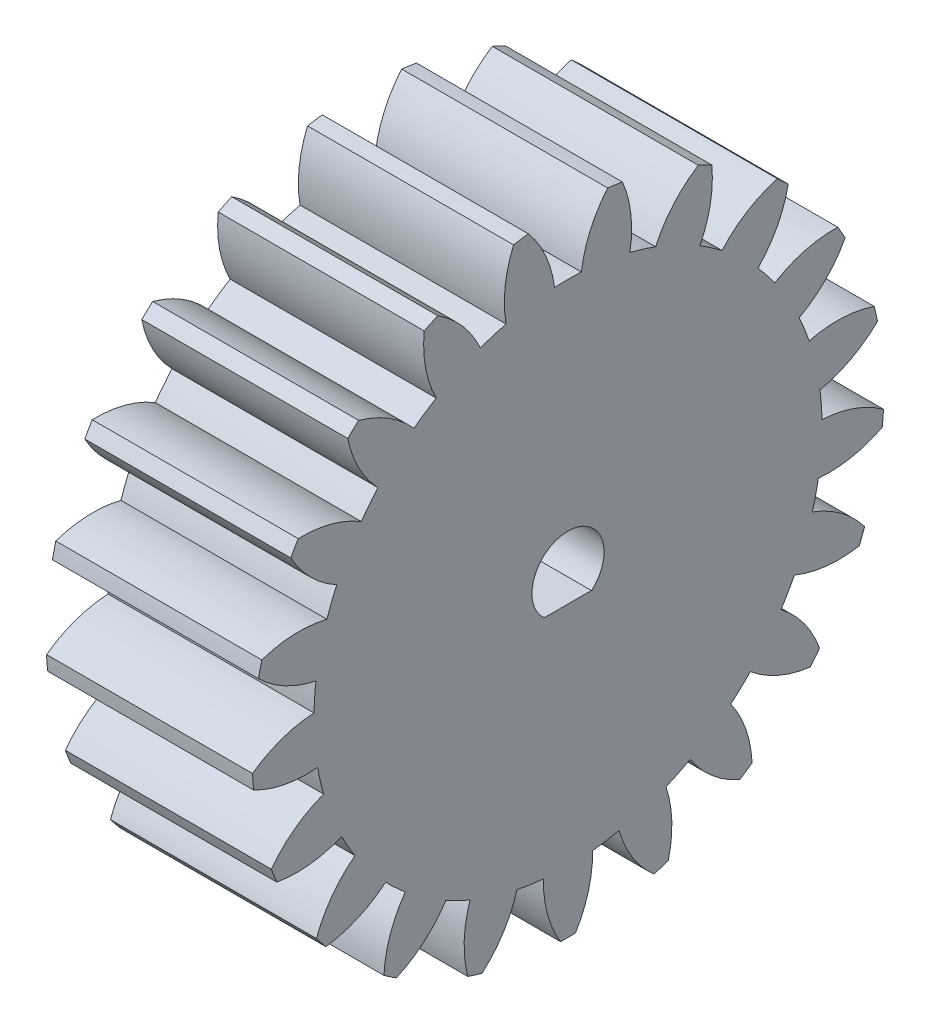
SolidWorks part; units mm, degrees
ref_plane "Plane1" through (0, 0, 0) normal (0, 0, 1) x (1, 0, 0)
ref_plane "Plane2" through (0, 0, 0) normal (0, 1, 0) x (1, 0, 0)
ref_plane "Plane3" through (0, 0, 0) normal (1, 0, 0) x (0, 0, -1)
other "Configuration Table"
sketch "HoldingSke" plane through (0, 0, 0) normal (0, 1, 0) x (1, 0, 0)
  line L0 (0, 0) -> (0.4668, -0.1792)
  line L1 (-15, 0) -> (100, 0) construction
  line L2 (0, 0) -> (-2.1039, 2.3779)
  line L3 (0, 0) -> (-11.863, 4.5341)
  line L4 (0, 0) -> (8.0624, 3.0949)
  line L5 (0, 0) -> (-46.8476, -17.4728)
  line L6 (0, 0) -> (-12.4344, -8.3896)
  line L7 (-2.1039, 2.3779) -> (8.6586, 51.2059)
  line L8 (-76.2, 54.61) -> (-75.3, 54.61)
  line L9 (-71.009, 38.7566) -> (-53.1078, 45.2721)
  line L10 (-76.2, 71.12) -> (104.1128, 71.12)
  line L11 (0, 0) -> (-15, 0)
  line L12 (-76.2, 101.6) -> (-76.133, 101.6)
  line L13 (24.9733, 27.94) -> (52.9518, 28.4284)
  line L14 (24.9733, 27.94) -> (24.9743, 27.94)
  line L15 (24.9733, 27.94) -> (100.4006, 29.5858)
  line L16 (-63.627, -2) -> (-12.827, -2)
  circle A0 centre (0, 0) radius 2.5
  circle A1 centre (0, 0) radius 18.499
  circle A2 centre (0, 0) radius 37.5
  circle A3 centre (0, 0) radius 2.5
  dimension "MHD" = 36.998
  dimension "Hub_dia" = 75
  dimension "Bore" = 5
  dimension "MBD" = 5
  dimension "Num_teeth" = 21
  dimension "Pitch" = 0.5
  dimension "Overall_len" = 50
  dimension "Show_teeth" = 21
  dimension "Thickness" = 15
  dimension "OAL" = 50.0001
  dimension "T_dim" = 0.9
  dimension "Ap" = 20
  dimension "H" = 19.05
  dimension "Pitch_radius" = 180.3128
  dimension "Width" = 15
  dimension "Backlash" = 0.067
  dimension "Addendum_fac" = 1
  dimension "Dedendum_fac" = 1.25
  dimension "Clearance_fac" = 0.25
  dimension "Dedendum_add" = 0.001
  dimension "Module" = 2
sketch "BasProSke" plane through (0, 0, 0) normal (0, 1, 0) x (1, 0, 0)
  line L0 (-10, 0) -> (60, 0) construction
  line L1 (0, 0) -> (0, 23)
  line L2 (0, 0) -> (15, 0)
  line L3 (15, 0) -> (15, 23)
  line L4 (15, 23) -> (0, 23)
  dimension "Thickness" = 15
  dimension "Diameter" = 46
revolve "Base-Revolve" add sketch "BasProSke" angle 360 about L0
sketch "TooCutSke" plane through (0, 0, 0) normal (1, 0, 0) x (0, 0, -1)
  line L1 (0, 0) -> (0, 107) construction
  line L2 (0, 0) -> (-1.6865, 20.9322) construction
  line L3 (0, 0) -> (-6.2448, 41.4315) construction
  line L4 (-1.6865, 20.9322) -> (-3.1224, 20.7157) construction
  arc A0 (0.9768, 18.4732) -> (-0.9768, 18.4732) centre (0, 0) ccw
  arc A1 (2.908, 22.841) -> (-2.908, 22.841) centre (0, 0) ccw
  circle A2 centre (0, 0) radius 21 construction
  circle A3 centre (0, 0) radius 19.7335 construction
  arc A4 (-0.9768, 18.4732) -> (-2.908, 22.841) centre (-9.308, 17.4004) ccw
  arc A5 (2.908, 22.841) -> (0.9768, 18.4732) centre (9.308, 17.4004) ccw
  dimension "Root_dia" = 36.998
  dimension "Overcut_dia" = 46.0508
  dimension "Pitch_dia" = 42
  dimension "Base_dia" = 39.4671
  dimension "Flank_rad" = 8.4
  dimension "Half_ang" = 8.571
  dimension "Half_CT" = 1.4521
extrude "ToothCut" cut sketch "TooCutSke" along normal through all
fillet "Breaks" [suppressed] radius 0.04
fillet "RootFillets" [suppressed] radius 0.501
pattern_circular "TeethCuts" count 21 every 17.143 about axis through (-10, 0, 0) along (1, 0, 0) of "ToothCut", "RootFillets", "Breaks"
sketch "HubNeaOneSke" plane through (0, 0, 0) normal (-1, 0, 0) x (0, 0, 1)
  circle A0 centre (0, 0) radius 18.499
  dimension "Diameter" = 36.998
extrude "HubNearOne" [suppressed] add sketch "HubNeaOneSke" along normal blind 35.0001
sketch "HubNeaBotSke" plane through (0, 0, 0) normal (-1, 0, 0) x (0, 0, 1)
  circle A0 centre (0, 0) radius 18.499
  dimension "Diameter" = 36.998
extrude "HubNearBoth" [suppressed] add sketch "HubNeaBotSke" along normal blind 17.5
ref_plane "FarPln" through (15, 0, 0) normal (1, 0, 0) x (0, 0, -1)
sketch "HubFarSke" plane through (15, 0, 0) normal (1, 0, 0) x (0, 0, -1)
  circle A0 centre (0, 0) radius 18.499
  dimension "Diameter" = 36.998
extrude "HubFar" [suppressed] add sketch "HubFarSke" along normal blind 17.5
sketch "BorSke" plane through (0, 0, 0) normal (1, 0, 0) x (0, 0, -1)
  circle A0 centre (0, 0) radius 2.5
  dimension "Diameter" = 5
extrude "Bore" cut sketch "BorSke" along normal mid plane 100.0001
sketch "KeySke" plane through (0, 0, 0) normal (1, 0, 0) x (0, 0, -1)
  line L0 (-1, 0) -> (-1, 3.4)
  line L1 (-1, 3.4) -> (1, 3.4)
  line L2 (1, 3.4) -> (1, 0)
  line L3 (0, 0) -> (0, 34) construction
  line L4 (-1, 0) -> (1, 0)
  dimension "Offset" = 3.4
  dimension "Width" = 2
extrude "Keyway" [suppressed] cut sketch "KeySke" along normal mid plane 100.0001
pattern_circular "Keyway2" [suppressed] count 2 every 90 about axis through (-10, 0, 0) along (1, 0, 0)
sketch "草圖1" plane through (0, 0, 0) normal (-1, 0, 0) x (0, 0, 1)
  circle A0 centre (0, 0) radius 2.625
  dimension "D1" = 5.25
extrude "除料-伸長1" cut sketch "草圖1" against normal blind 15
sketch "草圖3" plane through (0, 0, 0) normal (-1, 0, 0) x (0, 0, 1)
  line L0 (-1.7045, -1.975) -> (1.7538, -1.975)
  line L1 (-1.7045, -1.975) -> (-1.7045, -2.8239)
  line L2 (-1.7045, -2.8239) -> (1.7538, -2.8239)
  line L3 (1.7538, -1.975) -> (1.7538, -2.8239)
  circle A0 centre (0, 0) radius 2.625 construction
  dimension "D1" = 4.6
extrude "填料-伸長1" add sketch "草圖3" against normal blind 15
equation "' \"Module@HoldingSke\" = 6.35"
equation "' \"Num_teeth@HoldingSke\" = 12"
equation "' \"Ap@HoldingSke\" =  20"
equation "' \"Ap@HoldingSke\" = 20"
equation "' \"Width@HoldingSke\" = 0.5 * 25.4"
equation "' \"Hub_dia@HoldingSke\"= 1 * 25.4"
equation "' \"Hub_dia@HoldingSke\" = 1 * 25.4"
equation "' \"Overall_len@HoldingSke\" = 1.0 * 25.4"
equation "' \"Bore@HoldingSke\" = 0.75 * 25.4"
equation "' \"T_dim@HoldingSke\" = 0.1 * 25.4"
equation "' \"Width@KeySke\" = 0.25 * 25.4"
equation "' \"Show_teeth@HoldingSke\" = 13"
equation "' \"Backlash@HoldingSke\" = 0.009 * 25.4"
equation "' \"Addendum_fac@HoldingSke\" = 1.0"
equation "' \"Dedendum_fac@HoldingSke\" = 1.25"
equation "' \"Dedendum_add@HoldingSke\" = 0.00005 * 25.4"
equation "' \"Clearance_fac@HoldingSke\" = 0.25"
equation "\"Pitch@HoldingSke\" = 1 / \"Module@HoldingSke\""
equation "\"Overcut_dia@TooCutSke\" = (\"Num_teeth@HoldingSke\" + 2 * \"Addendum_fac@HoldingSke\") / \"Pitch@HoldingSke\" + 0.002 * 25.4"
equation "\"Pitch_dia@TooCutSke\" = \"Num_teeth@HoldingSke\" / \"Pitch@HoldingSke\""
equation "\"Base_dia@TooCutSke\" = \"Num_teeth@HoldingSke\" / \"Pitch@HoldingSke\" * cos((\"Ap@HoldingSke\"  * 3.14159265 / 180))"
equation "\"Root_dia@TooCutSke\" = (\"Num_teeth@HoldingSke\" + 2) / \"Pitch@HoldingSke\" - 2 * (\"Addendum_fac@HoldingSke\" + \"Dedendum_fac@HoldingSke\") / \"Pitch@HoldingSke\" - \"Dedendum_add@HoldingSke\" * 2"
equation "\"Half_ang@TooCutSke\" = 180 / \"Num_teeth@HoldingSke\""
equation "\"Half_CT@TooCutSke\" = \"Num_teeth@HoldingSke\" / \"Pitch@HoldingSke\" * sin((3.14159265 / 2 / \"Num_teeth@HoldingSke\")) / 2 - 7 * \"Backlash@HoldingSke\" / 4"
equation "\"Flank_rad@TooCutSke\" = \"Num_teeth@HoldingSke\" / \"Pitch@HoldingSke\" / 5"
equation "\"Radius@RootFillets\" = \"Clearance_fac@HoldingSke\" / \"Pitch@HoldingSke\" + \"Dedendum_add@HoldingSke\""
equation "\"Break_rad@Breaks\" = 0.02 / \"Pitch@HoldingSke\""
equation "\"Thickness@HoldingSke\" = \"Width@HoldingSke\""
equation "\"OAL@HoldingSke\" = \"Thickness@HoldingSke\""
equation "\"MHD@HoldingSke\" = (\"Num_teeth@HoldingSke\" + 2) / \"Pitch@HoldingSke\" - 2 * (\"Addendum_fac@HoldingSke\" + \"Dedendum_fac@HoldingSke\")  / \"Pitch@HoldingSke\" - \"Dedendum_add@HoldingSke\" * 2"
equation "\"MBD@HoldingSke\" = (\"Num_teeth@HoldingSke\" + 2) / \"Pitch@HoldingSke\" - 2 * (\"Addendum_fac@HoldingSke\" + \"Dedendum_fac@HoldingSke\")  / \"Pitch@HoldingSke\" - \"Dedendum_add@HoldingSke\" * 2 - 0.002 * 25.4"
equation "\"MHD@HoldingSke\" = ((sgn( \"MHD@HoldingSke\" - \"Hub_dia@HoldingSke\" )-1)*( \"MHD@HoldingSke\" - \"Hub_dia@HoldingSke\" ))/-2+ \"Hub_dia@HoldingSke\""
equation "\"MBD@HoldingSke\" = ((sgn( \"MBD@HoldingSke\" - \"Bore@HoldingSke\" )-1)*( \"MBD@HoldingSke\" - \"Bore@HoldingSke\" ))/-2+ \"Bore@HoldingSke\""
equation "\"OAL@HoldingSke\" = ((sgn( \"OAL@HoldingSke\" - \"Overall_len@HoldingSke\" )+1)*( \"OAL@HoldingSke\" - \"Overall_len@HoldingSke\" ))/2 + \"Overall_len@HoldingSke\" + 0.000002 * 25.4"
equation "\"Num_teeth@TeethCuts\" = int( \"Show_teeth@HoldingSke\" ) + 1"
equation "\"Num_teeth@TeethCuts\" = ((sgn( \"Num_teeth@TeethCuts\" - \"Num_teeth@HoldingSke\" )-1)*( \"Num_teeth@TeethCuts\" - \"Num_teeth@HoldingSke\" ))/-2+ \"Num_teeth@HoldingSke\""
equation "\"Num_teeth@TeethCuts\" = ((sgn( \"Num_teeth@TeethCuts\" - 2.0)+1)*( \"Num_teeth@TeethCuts\" - 2.0))/2 +2.0"
equation "\"Angle@TeethCuts\" = 360.0 / \"Num_teeth@HoldingSke\""
equation "\"Diameter@BasProSke\" = (\"Num_teeth@HoldingSke\" + 2 * \"Addendum_fac@HoldingSke\") / \"Pitch@HoldingSke\""
equation "\"Thickness@BasProSke\"  = \"Thickness@HoldingSke\""
equation "' \"Fillet_rad@BasProSke\" =  \"Thickness@HoldingSke\" * 0.05"
equation "' \"Fillet_rad@BasProSke\" = \"Thickness@HoldingSke\" * 0.05"
equation "\"MHD@HoldingSke\" = ((sgn( \"MHD@HoldingSke\" - \"Root_dia@TooCutSke\" )-1)*( \"MHD@HoldingSke\" - \"Root_dia@TooCutSke\" ))/-2+ \"Root_dia@TooCutSke\""
equation "\"Diameter@HubNeaOneSke\" = \"MHD@HoldingSke\""
equation "\"Length@HubNearOne\" = \"OAL@HoldingSke\" - \"Thickness@BasProSke\""
equation "\"Diameter@HubNeaBotSke\" = \"MHD@HoldingSke\""
equation "\"Length@HubNearBoth\" = ( \"OAL@HoldingSke\" - \"Thickness@BasProSke\" ) / 2.0"
equation "\"Thickness@FarPln\" = \"Thickness@BasProSke\""
equation "\"Diameter@HubFarSke\" = \"MHD@HoldingSke\""
equation "\"Length@HubFar\" = ( \"OAL@HoldingSke\" - \"Thickness@BasProSke\" ) / 2.0"
equation "\"Diameter@BorSke\" = \"MBD@HoldingSke\""
equation "\"D1@Bore\" = \"OAL@HoldingSke\" * 2.0"
equation "\"D1@Keyway\" = \"OAL@HoldingSke\" * 2.0"
equation "\"Offset@KeySke\" = \"T_dim@HoldingSke\" + \"MBD@HoldingSke\" / 2.0"
